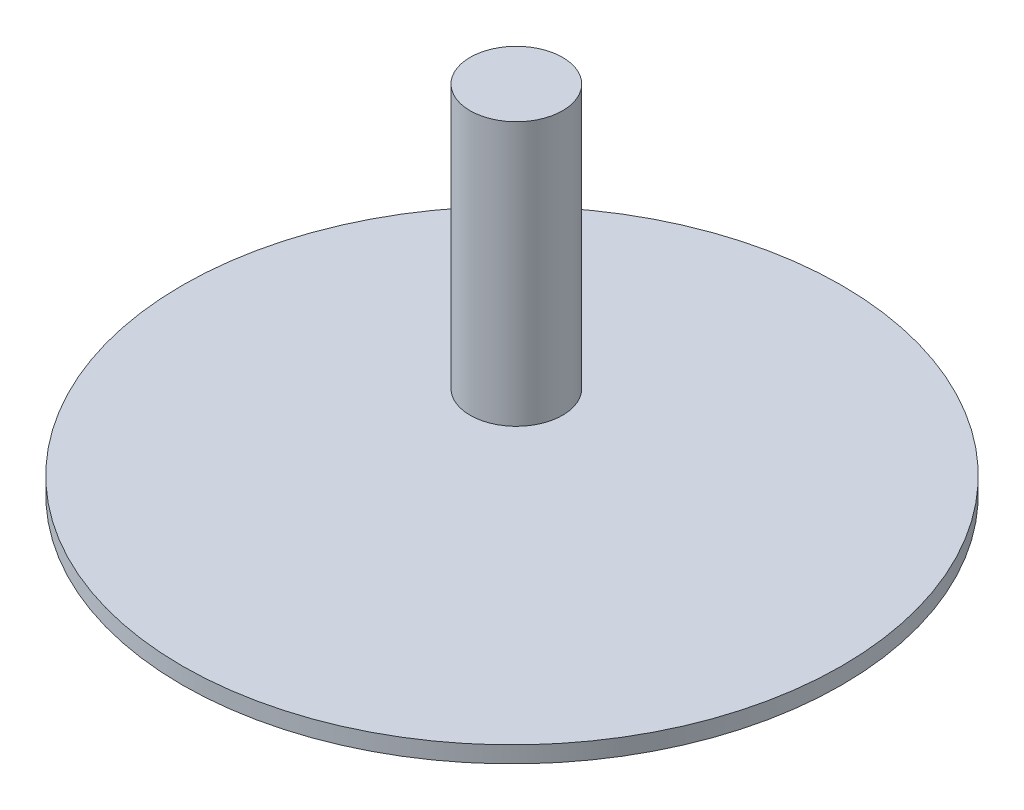
SolidWorks part; units mm, degrees
ref_plane "Front Plane" through (0, 0, 0) normal (0, 0, 1) x (1, 0, 0)
ref_plane "Top Plane" through (0, 0, 0) normal (0, 1, 0) x (1, 0, 0)
ref_plane "Right Plane" through (0, 0, 0) normal (1, 0, 0) x (0, 0, -1)
sketch "Sketch2" plane through (0, 0, 0) normal (0, 1, 0) x (1, 0, 0)
  circle A0 centre (0, 0) radius 101.6
extrude "Boss-Extrude1" add sketch "Sketch2" along normal blind 5.08
sketch "Sketch3" plane through (0, 5.08, 0) normal (0, 1, 0) x (1, 0, 0)
  circle A0 centre (-22.565, 23.9082) radius 14.25
extrude "Boss-Extrude2" add sketch "Sketch3" along normal blind 81.28
